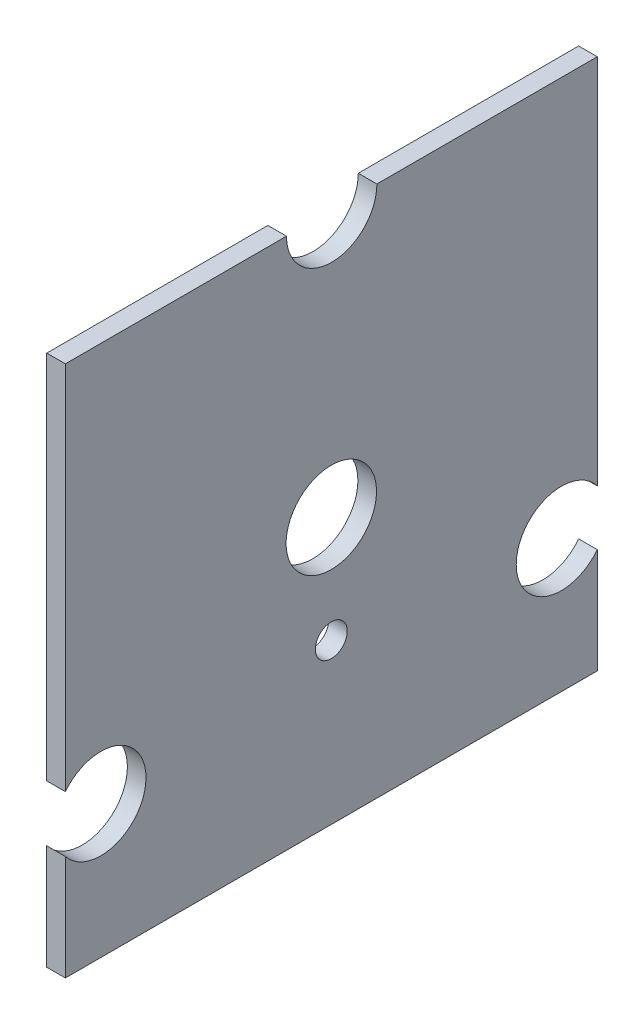
SolidWorks part; units mm, degrees
material "Tungsten"
ref_plane "Ebene vorne" through (0, 0, 0) normal (0, 0, 1) x (1, 0, 0)
ref_plane "Ebene oben" through (0, 0, 0) normal (0, 1, 0) x (1, 0, 0)
ref_plane "Ebene rechts" through (0, 0, 0) normal (1, 0, 0) x (0, 0, -1)
sketch "Sketch2" plane through (0, 0, 0) normal (1, 0, 0) x (0, 0, -1)
  line L0 (0, 50) -> (0, -50) construction
  line L1 (-50, 50) -> (50, 50)
  line L2 (-50, 50) -> (-50, -50)
  line L3 (-50, -50) -> (50, -50)
  line L4 (50, 50) -> (50, -50)
  line L5 (-50, 0) -> (50, 0) construction
  line L7 (-50, 50) -> (50, -50) construction
  circle A0 centre (0, 0) radius 8.5
  point P19 (0, 0)
  point P20 (0, 0)
  point P21 (0, 0)
  dimension "D3" = 17
  dimension "D1" = 100
  dimension "D2" = 100
extrude "Boss-Extrude1" add sketch "Sketch2" along normal blind 3.5
sketch "Sketch3" plane through (0, 0, 0) normal (-1, 0, 0) x (0, 0, 1)
  circle A0 centre (43.337, -24.9381) radius 8.5
  circle A1 centre (-43.2655, -25.0619) radius 8.5
  circle A2 centre (-0.0715, 49.9999) radius 8.5
  point P9 (0, 0)
  dimension "D1" = 17
  dimension "D2" = 50
  dimension "D3" = 3
extrude "Cut-Extrude1" cut sketch "Sketch3" against normal through all
sketch "Sketch4" plane through (0, 0, 0) normal (-1, 0, 0) x (0, 0, 1)
  circle A0 centre (0, -20) radius 3
  dimension "D1" = 6
  dimension "D2" = 20
extrude "Cut-Extrude2" cut sketch "Sketch4" against normal through all
